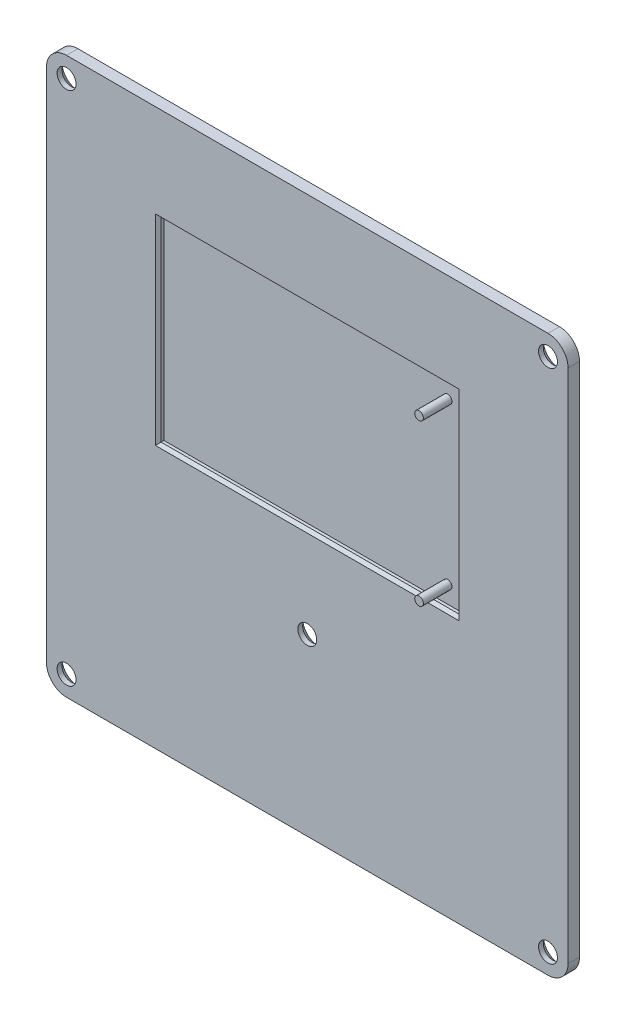
SolidWorks part; units mm, degrees
ref_plane "前视基准面" through (0, 0, 0) normal (0, 0, 1) x (1, 0, 0)
ref_plane "上视基准面" through (0, 0, 0) normal (0, 1, 0) x (1, 0, 0)
ref_plane "右视基准面" through (0, 0, 0) normal (1, 0, 0) x (0, 0, -1)
sketch "草图1" plane through (0, 0, 0) normal (0, 0, 1) x (1, 0, 0)
  line L1 (-42, 48.5) -> (42, 48.5)
  line L2 (-45.5, 45) -> (-45.5, -45)
  line L3 (-42, -48.5) -> (42, -48.5)
  line L4 (45.5, 45) -> (45.5, -45)
  line L5 (-45.5, 48.5) -> (45.5, -48.5) construction
  line L6 (-45.5, -48.5) -> (45.5, 48.5) construction
  arc A0 (-45.5, -45) -> (-42, -48.5) centre (-42, -45) ccw
  arc A1 (42, -48.5) -> (45.5, -45) centre (42, -45) ccw
  arc A2 (42, 48.5) -> (45.5, 45) centre (42, 45) cw
  arc A3 (-42, 48.5) -> (-45.5, 45) centre (-42, 45) ccw
  point P0 (0, 0)
  dimension "D3" = 3.5
  dimension "D1" = 97
  dimension "D2" = 91
extrude "凸台-拉伸1" add sketch "草图1" against normal blind 2
hole_wizard "打孔尺寸开槽半沉头螺钉的类型2" positions "3D草图2" profile "草图3" countersink size "M3" standard "GB"
sketch3d "3D草图2"
  line L0 (42, 45, -2) -> (42, 45, 0) construction
  line L1 (-42, 45, -2) -> (-42, 45, 0) construction
  line L2 (-42, -45, -2) -> (-42, -45, 0) construction
  line L3 (42, -45, -2) -> (42, -45, 0) construction
  point P0 (42, 45, -2)
  point P4 (-42, 45, -2)
  point P8 (-42, -45, -2)
  point P12 (42, -45, -2)
sketch "草图3" plane through (42, 45, -2) normal (1, 0, 0) x (0, 1, 0)
  line L0 (0, 0) -> (0, 15.9914)
  line L1 (0, 15.9914) -> (1.65, 15)
  line L2 (1.65, 15) -> (1.65, 1.15)
  line L3 (1.65, 1.15) -> (2.8, 0)
  line L5 (2.8, 0) -> (0, 0)
  line L6 (-1.65, 1.15) -> (-2.8, 0) construction
  line L10 (0, 15.9914) -> (-1.65, 15) construction
  line L11 (0, -6.35) -> (0, 107.95) construction
  dimension "孔直径" = 3.3
  dimension "孔深度" = 15
  dimension "近端锥形沉头孔直径" = 5.6
  dimension "近端锥形沉头孔角度" = 90
  dimension "导头角度" = 118
sketch "草图5" plane through (0, 0, -2) normal (0, 0, -1) x (-1, 0, 0)
  line L0 (0, 0) -> (0, 43.5111) construction
  line L1 (-19.7913, 30.8517) -> (19.9919, 30.8517) construction
  text T0 "Ruige"
extrude "凸台-拉伸3" add sketch "草图5" along normal blind 0.2
sketch "草图6" plane through (0, 0, -2) normal (0, 0, -1) x (-1, 0, 0)
  line L0 (0, 49.6356) -> (0, -18.6476) construction
hole_wizard "打孔尺寸开槽半沉头螺钉的类型3" positions "3D草图3" profile "草图7" countersink size "M3" standard "GB"
sketch3d "3D草图3"
  line L0 (0, 49.6356, -2) -> (0, -18.6476, -2) construction
  line L1 (42, 48.5, -2) -> (-42, 48.5, -2) construction
  point P0 (0, -18, -2)
  dimension "D1" = 66.5
sketch "草图7" plane through (0, -18, -2) normal (1, 0, 0) x (0, 1, 0)
  line L0 (0, 0) -> (0, 15.9914)
  line L1 (0, 15.9914) -> (1.65, 15)
  line L2 (1.65, 15) -> (1.65, 1.15)
  line L3 (1.65, 1.15) -> (2.8, 0)
  line L5 (2.8, 0) -> (0, 0)
  line L6 (-1.65, 1.15) -> (-2.8, 0) construction
  line L10 (0, 15.9914) -> (-1.65, 15) construction
  line L11 (0, -6.35) -> (0, 107.95) construction
  dimension "孔直径" = 3.3
  dimension "孔深度" = 15
  dimension "近端锥形沉头孔直径" = 5.6
  dimension "近端锥形沉头孔角度" = 90
  dimension "导头角度" = 118
sketch "草图8" plane through (0, 0, 0) normal (0, 0, 1) x (1, 0, 0)
  line L0 (0, 0) -> (0, 40.4032) construction
  line L2 (-26, 31.8084) -> (26, 31.8084)
  line L3 (-26, 31.8084) -> (-26, -2.1916)
  line L4 (-26, -2.1916) -> (26, -2.1916)
  line L5 (26, 31.8084) -> (26, -2.1916)
  line L6 (-26, 31.8084) -> (26, -2.1916) construction
  line L7 (-26, -2.1916) -> (26, 31.8084) construction
  point P3 (0, 14.8084)
  dimension "D1" = 52
  dimension "D2" = 34
extrude "切除-拉伸1" cut sketch "草图8" against normal blind 1
chamfer "倒角1" distance 0.5 angle 45 4 edges at (0, -2.1916, 0) (26, 14.8084, 0) (0, 31.8084, 0) (-26, 14.8084, 0)
sketch "草图9" plane through (0, 0, -1) normal (0, 0, 1) x (1, 0, 0)
  line L0 (26, 14.8084) -> (-17.7968, 14.8084) construction
  line L1 (26, -2.1916) -> (26, 31.8084) construction
  line L2 (23.5, 14.8084) -> (23.5, 29.9586) construction
  circle A0 centre (23.5, 28.8084) radius 0.75
  circle A1 centre (23.5, 0.8084) radius 0.75
  dimension "D3" = 1.5
  dimension "D1" = 2.5
  dimension "D2" = 28
extrude "凸台-拉伸4" add sketch "草图9" along normal blind 5
